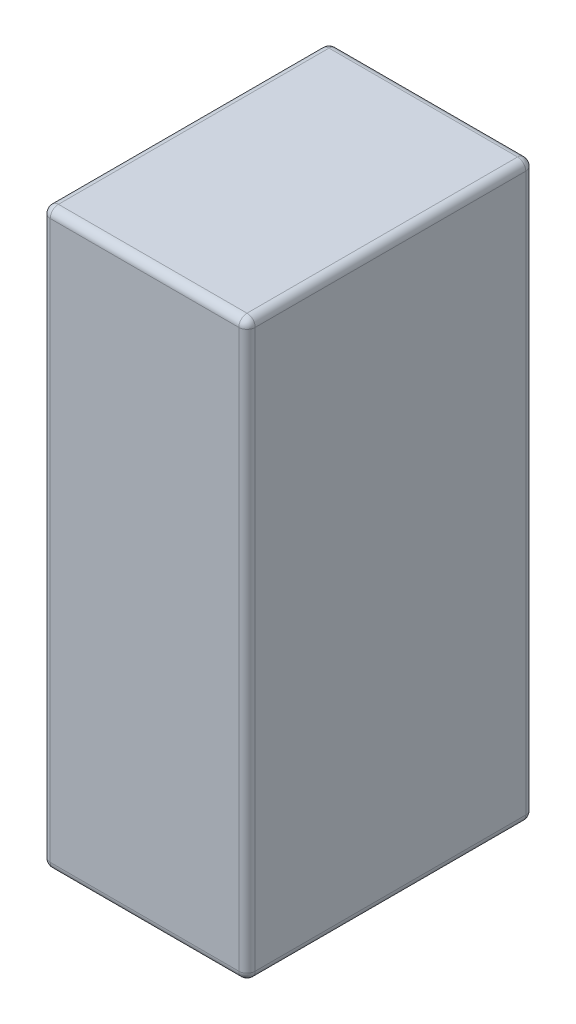
SolidWorks part; units mm, degrees
ref_plane "Front Plane" through (0, 0, 0) normal (0, 0, 1) x (1, 0, 0)
ref_plane "Top Plane" through (0, 0, 0) normal (0, 1, 0) x (1, 0, 0)
ref_plane "Right Plane" through (0, 0, 0) normal (1, 0, 0) x (0, 0, -1)
sketch "Sketch1" plane through (0, 0, 0) normal (0, 1, 0) x (1, 0, 0)
  line L1 (0, 0) -> (25, 0)
  line L2 (0, 0) -> (0, 35)
  line L3 (0, 35) -> (25, 35)
  line L4 (25, 0) -> (25, 35)
  dimension "D1" = 35
  dimension "D2" = 25
extrude "Boss-Extrude1" add sketch "Sketch1" along normal blind 70
fillet "Fillet1" radius 1 12 edges at (0, 35, 0) (25, 35, 0) (25, 35, -35) (0, 35, -35) (12.5, 70, -35) (25, 70, -17.5) (12.5, 70, 0) (0, 70, -17.5) (12.5, 0, -35) (25, 0, -17.5) (12.5, 0, 0) (0, 0, -17.5)
